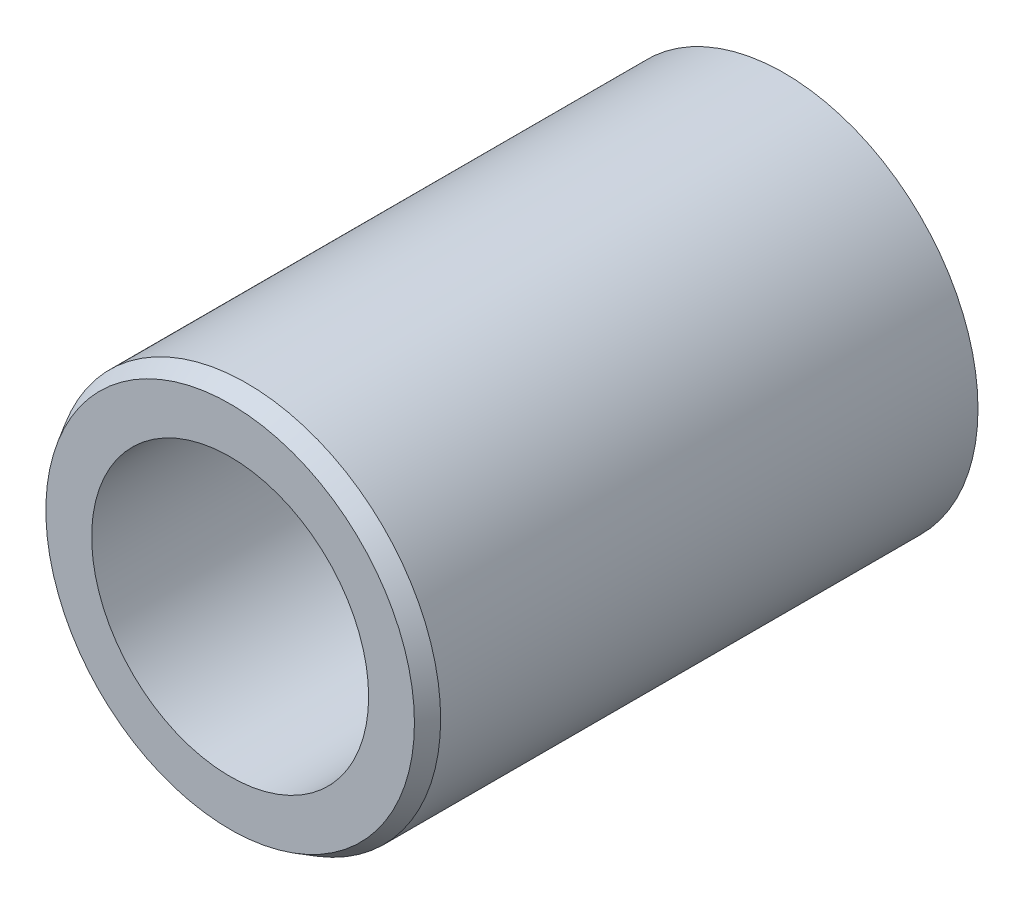
SolidWorks part; units mm, degrees
ref_plane "Front Plane" through (0, 0, 0) normal (0, 0, 1) x (1, 0, 0)
ref_plane "Top Plane" through (0, 0, 0) normal (0, 1, 0) x (1, 0, 0)
ref_plane "Right Plane" through (0, 0, 0) normal (1, 0, 0) x (0, 0, -1)
sketch "Sketch1" plane through (0, 0, 0) normal (0, 1, 0) x (1, 0, 0)
  line L0 (2.7887, 0) -> (2.5, -0.5)
  line L1 (2.5, -0.5) -> (2.5, -10)
  line L2 (2.5, -10) -> (3.3268, -10)
  line L3 (3.3268, -10) -> (3.5, -9.7)
  line L4 (3.5, -9.7) -> (3.5, 0)
  line L5 (3.5, 0) -> (2.7887, 0)
  line L6 (0, 0) -> (0, -10) construction
revolve "Revolve1" add sketch "Sketch1" angle 360 about L6
